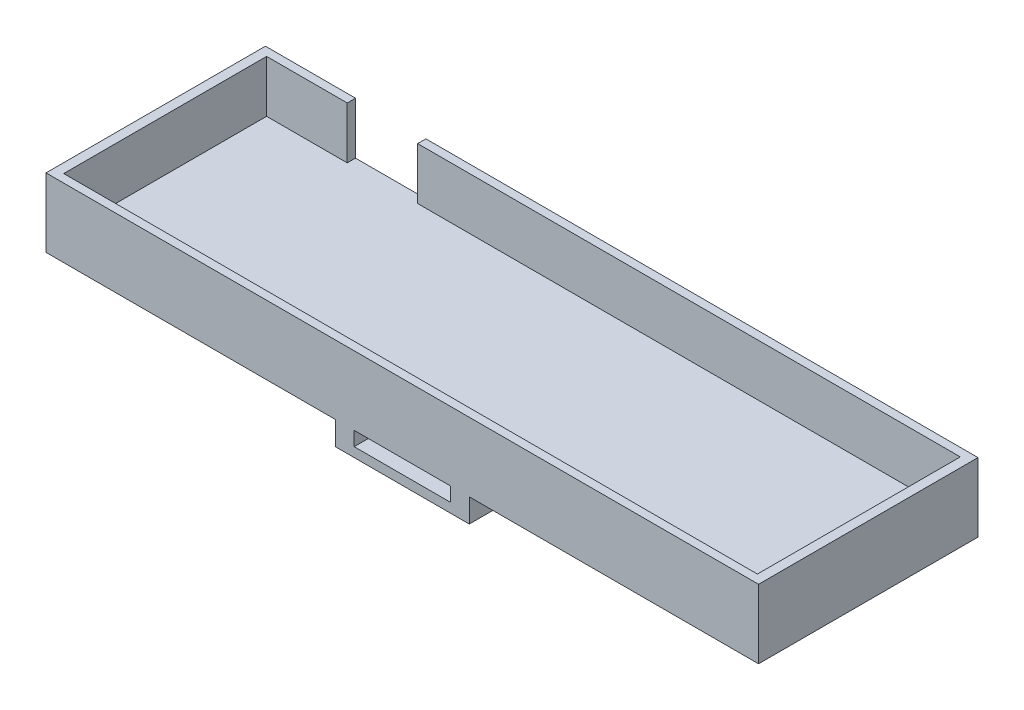
SolidWorks part; units mm, degrees
ref_plane "前视基准面" through (0, 0, 0) normal (0, 0, 1) x (1, 0, 0)
ref_plane "上视基准面" through (0, 0, 0) normal (0, 1, 0) x (1, 0, 0)
ref_plane "右视基准面" through (0, 0, 0) normal (1, 0, 0) x (0, 0, -1)
sketch "草图1" plane through (0, 0, 0) normal (0, 1, 0) x (1, 0, 0)
  line L1 (-75.5, 23.25) -> (75.5, 23.25)
  line L2 (-75.5, 23.25) -> (-75.5, -23.25)
  line L3 (-75.5, -23.25) -> (75.5, -23.25)
  line L4 (75.5, 23.25) -> (75.5, -23.25)
  line L5 (-75.5, 23.25) -> (75.5, -23.25) construction
  line L6 (-75.5, -23.25) -> (75.5, 23.25) construction
  point P0 (0, 0)
extrude "凸台-拉伸1" add sketch "草图1" along normal blind 14.6
sketch "草图5" plane through (0, 0, 0) normal (0, -1, 0) x (-1, 0, 0)
  line L0 (0, 0) -> (0, -13) construction
  line L1 (0, -13) -> (10.2, -23.25) construction
  line L2 (75.5, -23.25) -> (-75.5, -23.25) construction
  line L3 (-10.2, -10) -> (-14.2, -10)
  line L4 (10.2, -23.25) -> (14.2, -23.25)
  line L5 (10.2, -23.25) -> (10.2, -10)
  line L6 (10.2, -10) -> (14.2, -10)
  line L7 (14.2, -23.25) -> (14.2, -10)
  line L8 (-14.2, -23.25) -> (-14.2, -10)
  line L9 (-10.2, -23.25) -> (-14.2, -23.25)
  line L10 (-10.2, -23.25) -> (-10.2, -10)
  line L11 (0, 0) -> (-2, 0) construction
  line L12 (-10.2, 23.25) -> (-10.2, 10)
  line L13 (-10.2, 23.25) -> (-14.2, 23.25)
  line L14 (-14.2, 23.25) -> (-14.2, 10)
  line L15 (-10.2, 10) -> (-14.2, 10)
  line L16 (10.2, 10) -> (14.2, 10)
  line L17 (14.2, 23.25) -> (14.2, 10)
  line L18 (10.2, 23.25) -> (14.2, 23.25)
  line L19 (10.2, 23.25) -> (10.2, 10)
extrude "凸台-拉伸5" add sketch "草图5" along normal blind 3
sketch "草图8" plane through (0, -3, 0) normal (0, -1, 0) x (-1, 0, 0)
  line L1 (-14.2, 23.25) -> (14.2, 23.25)
  line L2 (-14.2, 23.25) -> (-14.2, -23.25)
  line L3 (-14.2, -23.25) -> (14.2, -23.25)
  line L4 (14.2, 23.25) -> (14.2, -23.25)
sketch "Sketch1" plane through (0, 14.6, 0) normal (0, 1, 0) x (1, 0, 0)
  line L1 (-73.5, -21.5) -> (73.5, -21.5)
  line L2 (-73.5, -21.5) -> (-73.5, 21.5)
  line L3 (-73.5, 21.5) -> (73.5, 21.5)
  line L4 (73.5, -21.5) -> (73.5, 21.5)
  line L5 (-73.5, -21.5) -> (73.5, 21.5) construction
  line L6 (-73.5, 21.5) -> (73.5, -21.5) construction
  point P0 (0, 0)
extrude "Cut-Extrude1" cut sketch "Sketch1" against normal blind 11
sketch "Sketch2" plane through (0, 14.6, 0) normal (0, 1, 0) x (1, 0, 0)
  line L0 (-75.5, 23.25) -> (-41.5, 23.25) construction
  line L1 (75.5, 23.25) -> (-75.5, 23.25) construction
  line L2 (-41.5, 23.25) -> (-56.4143, 23.25)
  line L3 (73.5, 21.5) -> (-73.5, 21.5) construction
  line L5 (-56.4143, 23.25) -> (-56.4143, 21.5)
  line L6 (-56.4143, 21.5) -> (-41.5, 21.5)
  line L7 (-41.5, 23.25) -> (-41.5, 21.5)
extrude "Cut-Extrude2" cut sketch "Sketch2" against normal blind 11
extrude "Boss-Extrude1" add sketch "草图8" along normal blind 2
